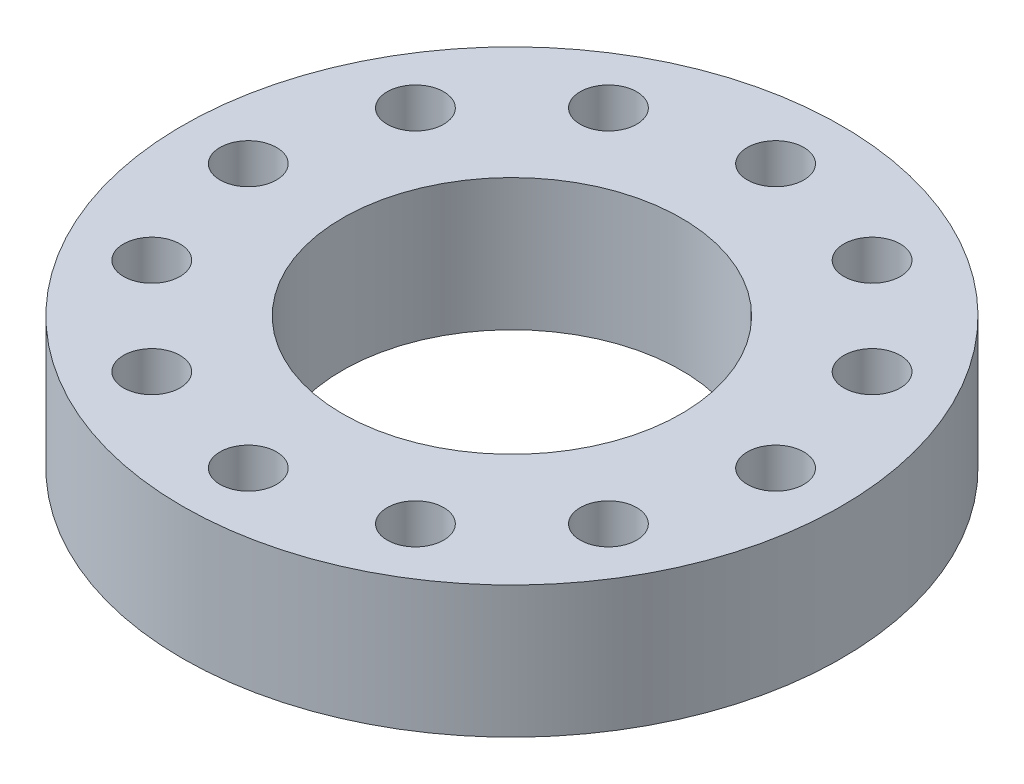
SolidWorks part; units mm, degrees
ref_plane "Front Plane" through (0, 0, 0) normal (0, 0, 1) x (1, 0, 0)
ref_plane "Top Plane" through (0, 0, 0) normal (0, 1, 0) x (1, 0, 0)
ref_plane "Right Plane" through (0, 0, 0) normal (1, 0, 0) x (0, 0, -1)
sketch "Sketch1" plane through (0, 0, 0) normal (0, 1, 0) x (1, 0, 0)
  circle A0 centre (0, 0) radius 17.5
  circle A1 centre (0, 0) radius 9
  circle A2 centre (0, 0) radius 14 construction
  circle A3 centre (0, 14) radius 1.5
  circle A4 centre (7, 12.1244) radius 1.5
  circle A5 centre (12.1244, 7) radius 1.5
  circle A6 centre (14, 0) radius 1.5
  circle A7 centre (12.1244, -7) radius 1.5
  circle A8 centre (7, -12.1244) radius 1.5
  circle A9 centre (0, -14) radius 1.5
  circle A10 centre (-7, -12.1244) radius 1.5
  circle A11 centre (-12.1244, -7) radius 1.5
  circle A12 centre (-14, 0) radius 1.5
  circle A13 centre (-12.1244, 7) radius 1.5
  circle A14 centre (-7, 12.1244) radius 1.5
  point P19 (0, 0)
  dimension "D1" = 35
  dimension "D2" = 18
  dimension "D3" = 28
  dimension "D4" = 3
  dimension "D5" = 12
extrude "Boss-Extrude1" add sketch "Sketch1" along normal blind 7
